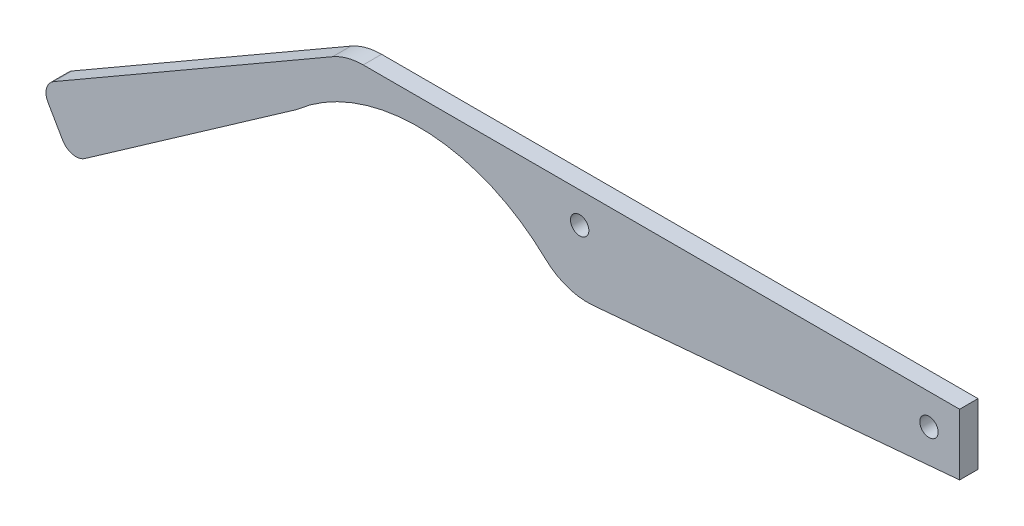
SolidWorks part; units mm, degrees
ref_plane "Front Plane" through (0, 0, 0) normal (0, 0, 1) x (1, 0, 0)
ref_plane "Top Plane" through (0, 0, 0) normal (0, 1, 0) x (1, 0, 0)
ref_plane "Right Plane" through (0, 0, 0) normal (1, 0, 0) x (0, 0, -1)
sketch "Sketch1" plane through (0, 0, 0) normal (0, 0, 1) x (1, 0, 0)
  line L0 (0, 0) -> (-97.3205, 0)
  line L1 (-102.3205, -1.3397) -> (-147.8349, -27.6175)
  line L2 (-148.75, -31.0326) -> (-146.3641, -35.165)
  line L3 (-142.7651, -35.9629) -> (-108.2496, -11.7949)
  line L4 (-59.8514, -15.2363) -> (0, -10)
  line L5 (0, -10) -> (0, 0)
  arc A0 (-108.0398, -11.6306) -> (-67.621, -12.5144) centre (-88.315, -34.2344) cw
  arc A1 (-67.621, -12.5144) -> (-59.8514, -15.2363) centre (-60.723, -5.2744) ccw
  arc A2 (-97.3205, 0) -> (-102.3205, -1.3397) centre (-97.3205, -10) ccw
  arc A3 (-108.2496, -11.7949) -> (-108.0398, -11.6306) centre (-109.6836, -9.747) ccw
  arc A4 (-147.8349, -27.6175) -> (-148.75, -31.0326) centre (-146.5849, -29.7826) ccw
  arc A5 (-146.3641, -35.165) -> (-142.7651, -35.9629) centre (-144.1991, -33.915) ccw
  point P14 (-64.7527, -15.6651)
  point P17 (-100, 0)
  point P20 (-108.1382, -11.7168)
  point P23 (-150, -28.8675)
  point P26 (-145, -37.5278)
  dimension "D7" = 30
  dimension "D11" = 10
  dimension "D12" = 2.5
  dimension "D1" = 150
  dimension "D2" = 100
  dimension "D3" = 150
  dimension "D4" = 10
  dimension "D5" = 85
  dimension "D6" = 45
  dimension "D8" = 95
  dimension "D9" = 10
  dimension "D10" = 65
extrude "Boss-Extrude1" add sketch "Sketch1" along normal blind 3
sketch "Sketch2" plane through (0, 0, 0) normal (0, 0, -1) x (-1, 0, 0)
  line L0 (0, 0) -> (97.3205, 0) construction
  line L1 (0, -10) -> (0, 0) construction
  circle A0 centre (5, -5) radius 1.5
  circle A1 centre (62, -5) radius 1.5
  point P6 (8.7388, -5)
  dimension "D1" = 3
  dimension "D2" = 3
  dimension "D3" = 57
  dimension "D4" = 5
  dimension "D5" = 5
  dimension "D6" = 5
extrude "Cut-Extrude1" cut sketch "Sketch2" against normal blind 10
